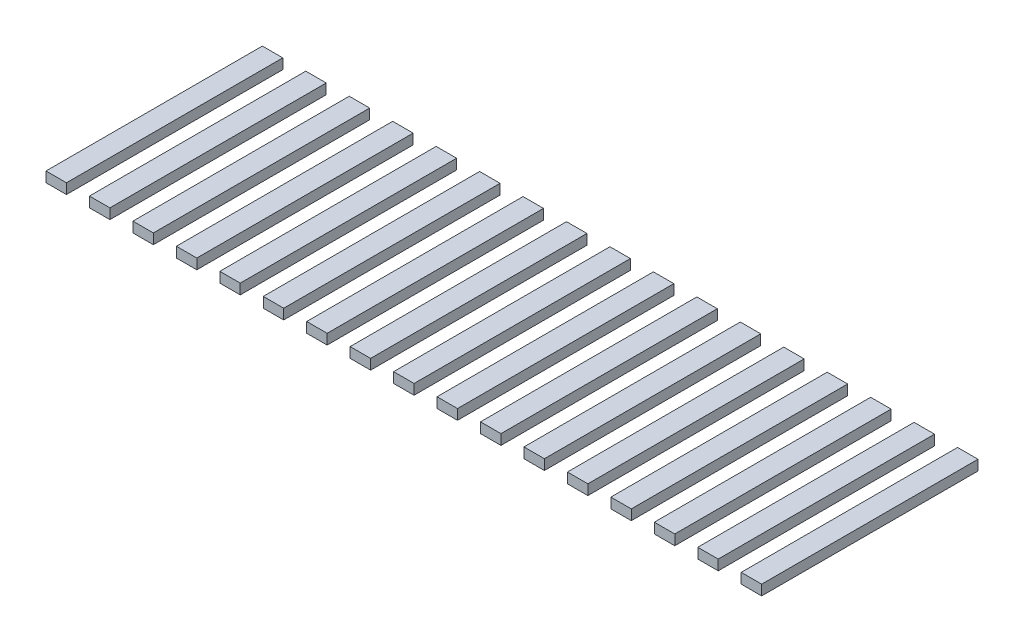
SolidWorks part; units mm, degrees
ref_plane "Спереди" through (0, 0, 0) normal (0, 0, 1) x (1, 0, 0)
ref_plane "Сверху" through (0, 0, 0) normal (0, 1, 0) x (1, 0, 0)
ref_plane "Справа" through (0, 0, 0) normal (1, 0, 0) x (0, 0, -1)
sketch "Sketch1" plane through (0, 0, 0) normal (0, 1, 0) x (1, 0, 0)
  line L0 (-49.9815, -14.9195) -> (-49.5815, -14.9195)
  line L1 (-50.8315, -14.9195) -> (-50.4315, -14.9195)
  line L2 (-50.8315, -14.9195) -> (-50.8315, -19.1517)
  line L3 (-50.8315, -19.1517) -> (-50.4315, -19.1517)
  line L4 (-50.4315, -14.9195) -> (-50.4315, -19.1517)
  line L5 (-49.9815, -14.9195) -> (-49.9815, -19.1517)
  line L6 (-49.9815, -19.1517) -> (-49.5815, -19.1517)
  line L7 (-49.5815, -14.9195) -> (-49.5815, -19.1517)
  line L8 (-49.1315, -14.9195) -> (-48.7315, -14.9195)
  line L9 (-49.1315, -14.9195) -> (-49.1315, -19.1517)
  line L10 (-49.1315, -19.1517) -> (-48.7315, -19.1517)
  line L11 (-48.7315, -14.9195) -> (-48.7315, -19.1517)
  line L12 (-48.2815, -14.9195) -> (-47.8815, -14.9195)
  line L13 (-48.2815, -14.9195) -> (-48.2815, -19.1517)
  line L14 (-48.2815, -19.1517) -> (-47.8815, -19.1517)
  line L15 (-47.8815, -14.9195) -> (-47.8815, -19.1517)
  line L16 (-47.4315, -14.9195) -> (-47.0315, -14.9195)
  line L17 (-47.4315, -14.9195) -> (-47.4315, -19.1517)
  line L18 (-47.4315, -19.1517) -> (-47.0315, -19.1517)
  line L19 (-47.0315, -14.9195) -> (-47.0315, -19.1517)
  line L20 (-46.5815, -14.9195) -> (-46.1815, -14.9195)
  line L21 (-46.5815, -14.9195) -> (-46.5815, -19.1517)
  line L22 (-46.5815, -19.1517) -> (-46.1815, -19.1517)
  line L23 (-46.1815, -14.9195) -> (-46.1815, -19.1517)
  line L24 (-45.7315, -14.9195) -> (-45.3315, -14.9195)
  line L25 (-45.7315, -14.9195) -> (-45.7315, -19.1517)
  line L26 (-45.7315, -19.1517) -> (-45.3315, -19.1517)
  line L27 (-45.3315, -14.9195) -> (-45.3315, -19.1517)
  line L28 (-44.8815, -14.9195) -> (-44.4815, -14.9195)
  line L29 (-44.8815, -14.9195) -> (-44.8815, -19.1517)
  line L30 (-44.8815, -19.1517) -> (-44.4815, -19.1517)
  line L31 (-44.4815, -14.9195) -> (-44.4815, -19.1517)
  line L32 (-44.0315, -14.9195) -> (-43.6315, -14.9195)
  line L33 (-44.0315, -14.9195) -> (-44.0315, -19.1517)
  line L34 (-44.0315, -19.1517) -> (-43.6315, -19.1517)
  line L35 (-43.6315, -14.9195) -> (-43.6315, -19.1517)
  line L36 (-43.1815, -14.9195) -> (-42.7815, -14.9195)
  line L37 (-43.1815, -14.9195) -> (-43.1815, -19.1517)
  line L38 (-43.1815, -19.1517) -> (-42.7815, -19.1517)
  line L39 (-42.7815, -14.9195) -> (-42.7815, -19.1517)
  line L40 (-42.3315, -14.9195) -> (-41.9315, -14.9195)
  line L41 (-42.3315, -14.9195) -> (-42.3315, -19.1517)
  line L42 (-42.3315, -19.1517) -> (-41.9315, -19.1517)
  line L43 (-41.9315, -14.9195) -> (-41.9315, -19.1517)
  line L44 (-41.4815, -14.9195) -> (-41.0815, -14.9195)
  line L45 (-41.4815, -14.9195) -> (-41.4815, -19.1517)
  line L46 (-41.4815, -19.1517) -> (-41.0815, -19.1517)
  line L47 (-41.0815, -14.9195) -> (-41.0815, -19.1517)
  line L48 (-40.6315, -14.9195) -> (-40.2315, -14.9195)
  line L49 (-40.6315, -14.9195) -> (-40.6315, -19.1517)
  line L50 (-40.6315, -19.1517) -> (-40.2315, -19.1517)
  line L51 (-40.2315, -14.9195) -> (-40.2315, -19.1517)
  line L52 (-39.7815, -14.9195) -> (-39.3815, -14.9195)
  line L53 (-39.7815, -14.9195) -> (-39.7815, -19.1517)
  line L54 (-39.7815, -19.1517) -> (-39.3815, -19.1517)
  line L55 (-39.3815, -14.9195) -> (-39.3815, -19.1517)
  line L56 (-38.9315, -14.9195) -> (-38.5315, -14.9195)
  line L57 (-38.9315, -14.9195) -> (-38.9315, -19.1517)
  line L58 (-38.9315, -19.1517) -> (-38.5315, -19.1517)
  line L59 (-38.5315, -14.9195) -> (-38.5315, -19.1517)
  line L60 (-38.0815, -14.9195) -> (-37.6815, -14.9195)
  line L61 (-38.0815, -14.9195) -> (-38.0815, -19.1517)
  line L62 (-38.0815, -19.1517) -> (-37.6815, -19.1517)
  line L63 (-37.6815, -14.9195) -> (-37.6815, -19.1517)
  line L64 (-37.2315, -14.9195) -> (-36.8315, -14.9195)
  line L65 (-37.2315, -14.9195) -> (-37.2315, -19.1517)
  line L66 (-37.2315, -19.1517) -> (-36.8315, -19.1517)
  line L67 (-36.8315, -14.9195) -> (-36.8315, -19.1517)
  dimension "D1" = 17
  dimension "D2" = 0.4
  dimension "D3" = 0.45
  dimension "D4" = 14
extrude "Boss-Extrude1" add sketch "Sketch1" along normal blind 0.2
